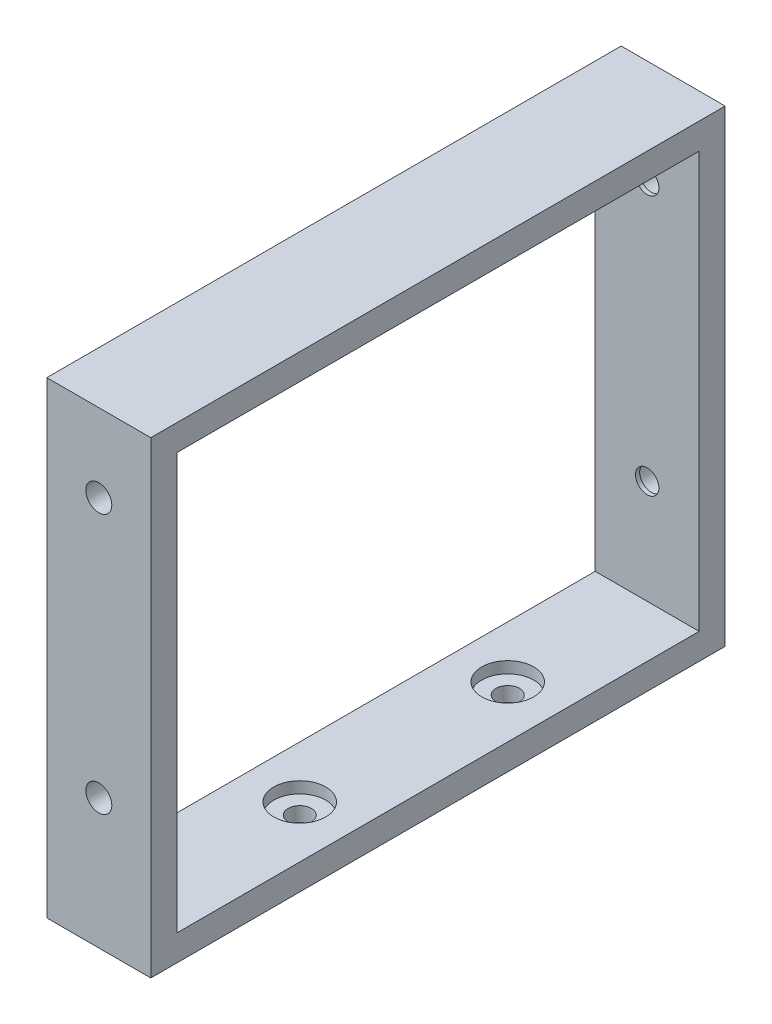
SolidWorks part; units mm, degrees
ref_plane "Front Plane" through (0, 0, 0) normal (0, 0, 1) x (1, 0, 0)
ref_plane "Top Plane" through (0, 0, 0) normal (0, 1, 0) x (1, 0, 0)
ref_plane "Right Plane" through (0, 0, 0) normal (1, 0, 0) x (0, 0, -1)
sketch "Sketch1" plane through (0, 0, 0) normal (1, 0, 0) x (0, 0, -1)
  line L1 (-55.2375, -45) -> (55.2375, -45)
  line L2 (-55.2375, -45) -> (-55.2375, 45)
  line L3 (-55.2375, 45) -> (55.2375, 45)
  line L4 (55.2375, -45) -> (55.2375, 45)
  line L5 (-55.2375, -45) -> (55.2375, 45) construction
  line L6 (-55.2375, 45) -> (55.2375, -45) construction
  line L7 (-50.2375, -40) -> (50.2375, -40)
  line L8 (-50.2375, -40) -> (-50.2375, 40)
  line L9 (-50.2375, 40) -> (50.2375, 40)
  line L10 (50.2375, -40) -> (50.2375, 40)
  line L11 (-50.2375, -40) -> (50.2375, 40) construction
  line L12 (-50.2375, 40) -> (50.2375, -40) construction
  line L13 (20.2375, -40) -> (25.2375, -40)
  line L14 (20.2375, -40) -> (20.2375, 40)
  line L15 (20.2375, 40) -> (25.2375, 40)
  line L16 (25.2375, -40) -> (25.2375, 40)
  line L17 (20.2375, -40) -> (25.2375, 40) construction
  line L18 (20.2375, 40) -> (25.2375, -40) construction
  point P0 (0, 0)
  point P6 (0, 0)
  point P11 (22.7375, 0)
  dimension "D1" = 110.475
  dimension "D2" = 90
  dimension "D3" = 5
  dimension "D4" = 5
  dimension "D5" = 5
  dimension "D6" = 25
extrude "Boss-Extrude1" add sketch "Sketch1" along normal blind 20 contours L1 L4 L3 L2 L10 L7 L8 L9 | L7 L16 L9 L14
hole_wizard "CBORE for M4 SBHCS1" positions "Sketch2" profile "Sketch3" counterbore size "M4" standard "ANSI Metric"
sketch "Sketch2" plane through (0, -40, 0) normal (0, 1, 0) x (1, 0, 0)
  line L0 (10, 23.4125) -> (10, -16.5875)
  line L2 (0, -55.2375) -> (0, 55.2375) construction
  point P1 (10, 23.4125)
  point P2 (10, -16.5875)
  dimension "D1" = 40
  dimension "D2" = 10
  dimension "D3" = 31.825
sketch "Sketch3" plane through (10, -40, -23.4125) normal (1, 0, 0) x (0, 0, 1)
  line L0 (0, 0) -> (0, 9.1519)
  line L1 (0, 9.1519) -> (2.25, 7.8)
  line L2 (2.25, 7.8) -> (2.25, 2.2)
  line L3 (2.25, 2.2) -> (5, 2.2)
  line L4 (5, 2.2) -> (5, 0)
  line L5 (5, 0) -> (0, 0)
  line L10 (0, 9.1519) -> (-2.25, 7.8) construction
  line L11 (0, -6.35) -> (0, 107.95) construction
  dimension "Hole Dia." = 4.5
  dimension "Hole Depth" = 7.8
  dimension "C'Bore Dia." = 10
  dimension "C'Bore Depth" = 2.2
  dimension "Drill Angle" = 118
hole_wizard "CBORE for M5 Hex Head Bolt1" positions "Sketch4" profile "Sketch6" counterbore size "M5" standard "ANSI Metric"
sketch "Sketch4" plane through (0, 0, 55.2375) normal (0, 0, 1) x (1, 0, 0)
  line L0 (10, 30) -> (10, -20)
  line L2 (0, -45) -> (0, 45) construction
  line L3 (20, -45) -> (0, -45) construction
  point P0 (10, 30)
  point P1 (10, -20)
  dimension "D1" = 50
  dimension "D2" = 10
  dimension "D3" = 25
sketch "Sketch6" plane through (10, 30, 55.2375) normal (1, 0, 0) x (0, -1, 0)
  line L0 (0, 0) -> (0, 11.4519)
  line L1 (0, 11.4519) -> (2.25, 10.1)
  line L2 (2.25, 10.1) -> (2.25, 4.2)
  line L3 (2.25, 4.2) -> (2.5, 4.2)
  line L4 (2.5, 4.2) -> (2.5, 0)
  line L5 (2.5, 0) -> (0, 0)
  line L10 (0, 11.4519) -> (-2.25, 10.1) construction
  line L11 (0, -6.35) -> (0, 107.95) construction
  dimension "Hole Dia." = 4.5
  dimension "Hole Depth" = 10.1
  dimension "C'Bore Dia." = 5
  dimension "C'Bore Depth" = 4.2
  dimension "Drill Angle" = 118
mirror "Mirror1" about plane through (0, 0, 0) normal (0, 0, 1) of "CBORE for M5 Hex Head Bolt1"
sketch "Sketch7" plane through (0, 0, 0) normal (-1, 0, 0) x (0, 0, 1)
  line L1 (-25.2375, 40) -> (-20.2375, 40)
  line L2 (-25.2375, 40) -> (-25.2375, -40)
  line L3 (-25.2375, -40) -> (-20.2375, -40)
  line L4 (-20.2375, 40) -> (-20.2375, -40)
extrude "Cut-Extrude1" cut sketch "Sketch7" against normal blind 30
